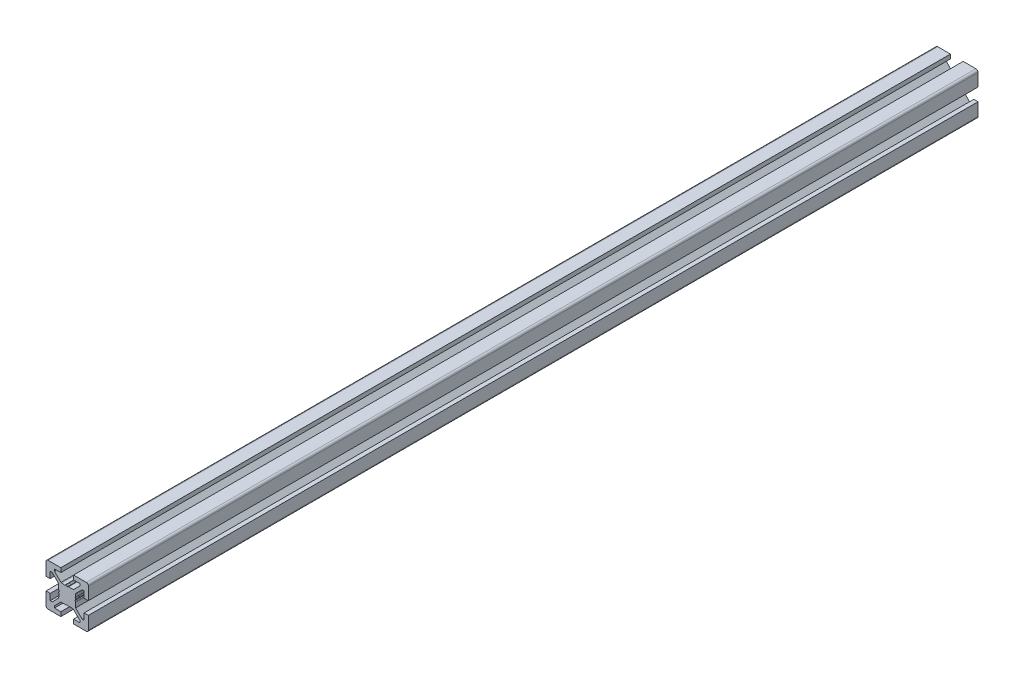
SolidWorks part; units mm, degrees
ref_plane "Front Plane" through (0, 0, 0) normal (0, 0, 1) x (1, 0, 0)
ref_plane "Top Plane" through (0, 0, 0) normal (0, 1, 0) x (1, 0, 0)
ref_plane "Right Plane" through (0, 0, 0) normal (1, 0, 0) x (0, 0, -1)
ref_plane "Plane1" through (0, 0, -2000) normal (0, 0, -1) x (-1, 0, 0)
sketch "Sketch1" plane through (0, 0, -2000) normal (0, 0, -1) x (-1, 0, 0)
  line L0 (10, -3) -> (8, -3)
  line L1 (8, -3) -> (8, -6)
  line L2 (8, -6) -> (7.0607, -6)
  line L3 (7.0607, -6) -> (4, -2.9393)
  line L4 (4, -2.9393) -> (4, -2.5)
  line L5 (4, -2.5) -> (3.751, -1.2189)
  line L6 (3.751, -1.2189) -> (3.933, -0.9036)
  line L7 (3.933, -0.4036) -> (3.7, 0)
  line L8 (3.7, 0) -> (3.933, 0.4036)
  line L9 (4, 0.6536) -> (4, 2.9393)
  line L10 (4, 2.9393) -> (7.0607, 6)
  line L11 (7.0607, 6) -> (8, 6)
  line L12 (8, 6) -> (8, 3)
  line L13 (8, 3) -> (10, 3)
  line L14 (10, 3) -> (10, 9)
  line L15 (9, 10) -> (3, 10)
  line L16 (3, 10) -> (3, 8)
  line L17 (3, 8) -> (6, 8)
  line L18 (6, 8) -> (6, 7.0607)
  line L19 (6, 7.0607) -> (2.9393, 4)
  line L20 (2.9393, 4) -> (2.5, 4)
  line L21 (2.5, 4) -> (1.2189, 3.751)
  line L22 (1.2189, 3.751) -> (0.9036, 3.933)
  line L23 (0.4036, 3.933) -> (0, 3.7)
  line L24 (0, 3.7) -> (-0.4036, 3.933)
  line L25 (-0.6536, 4) -> (-2.9393, 4)
  line L26 (-2.9393, 4) -> (-6, 7.0607)
  line L27 (-6, 7.0607) -> (-6, 8)
  line L28 (-6, 8) -> (-3, 8)
  line L29 (-3, 8) -> (-3, 10)
  line L30 (-3, 10) -> (-9, 10)
  line L31 (-10, 9) -> (-10, 3)
  line L32 (-10, 3) -> (-8, 3)
  line L33 (-8, 3) -> (-8, 6)
  line L34 (-8, 6) -> (-7.0607, 6)
  line L35 (-7.0607, 6) -> (-4, 2.9393)
  line L36 (-4, 2.9393) -> (-4, 2.5)
  line L37 (-4, 2.5) -> (-3.751, 1.2189)
  line L38 (-3.751, 1.2189) -> (-3.933, 0.9036)
  line L39 (-3.933, 0.4036) -> (-3.7, 0)
  line L40 (-3.7, 0) -> (-3.933, -0.4036)
  line L41 (-4, -0.6536) -> (-4, -2.9393)
  line L42 (-4, -2.9393) -> (-7.0607, -6)
  line L43 (-7.0607, -6) -> (-8, -6)
  line L44 (-8, -6) -> (-8, -3)
  line L45 (-8, -3) -> (-10, -3)
  line L46 (-10, -3) -> (-10, -9)
  line L47 (-9, -10) -> (-3, -10)
  line L48 (-3, -10) -> (-3, -8)
  line L49 (-3, -8) -> (-6, -8)
  line L50 (-6, -8) -> (-6, -7.0607)
  line L51 (-6, -7.0607) -> (-2.9393, -4)
  line L52 (-2.9393, -4) -> (-2.5, -4)
  line L53 (-2.5, -4) -> (-1.2189, -3.751)
  line L54 (-1.2189, -3.751) -> (-0.9036, -3.933)
  line L55 (-0.4036, -3.933) -> (0, -3.7)
  line L56 (0, -3.7) -> (0.4036, -3.933)
  line L57 (0.6536, -4) -> (2.9393, -4)
  line L58 (2.9393, -4) -> (6, -7.0607)
  line L59 (6, -7.0607) -> (6, -8)
  line L60 (6, -8) -> (3, -8)
  line L61 (3, -8) -> (3, -10)
  line L62 (3, -10) -> (9, -10)
  line L63 (10, -9) -> (10, -3)
  circle A0 centre (0, 0) radius 2.1
  arc A1 (3.933, -0.9036) -> (3.933, -0.4036) centre (3.5, -0.6536) ccw
  arc A2 (3.933, 0.4036) -> (4, 0.6536) centre (3.5, 0.6536) ccw
  arc A3 (10, 9) -> (9, 10) centre (9, 9) ccw
  arc A4 (0.9036, 3.933) -> (0.4036, 3.933) centre (0.6536, 3.5) ccw
  arc A5 (-0.4036, 3.933) -> (-0.6536, 4) centre (-0.6536, 3.5) ccw
  arc A6 (-9, 10) -> (-10, 9) centre (-9, 9) ccw
  arc A7 (-3.933, 0.9036) -> (-3.933, 0.4036) centre (-3.5, 0.6536) ccw
  arc A8 (-3.933, -0.4036) -> (-4, -0.6536) centre (-3.5, -0.6536) ccw
  arc A9 (-10, -9) -> (-9, -10) centre (-9, -9) ccw
  arc A10 (-0.9036, -3.933) -> (-0.4036, -3.933) centre (-0.6536, -3.5) ccw
  arc A11 (0.4036, -3.933) -> (0.6536, -4) centre (0.6536, -3.5) ccw
  arc A12 (9, -10) -> (10, -9) centre (9, -9) ccw
extrude "Boss-Extrude1" add sketch "Sketch1" against normal blind 400
sketch "草图1" plane through (0, 0, -1600) normal (0, 0, 1) x (1, 0, 0)
  line L64 (-10, -3) -> (-10, -9)
  line L65 (-8, -3) -> (-10, -3)
  line L66 (-8, -6) -> (-8, -3)
  line L67 (-7.0607, -6) -> (-8, -6)
  line L68 (-4, -2.9393) -> (-7.0607, -6)
  line L69 (-4, -2.5) -> (-4, -2.9393)
  line L70 (-3.751, -1.2189) -> (-4, -2.5)
  line L71 (-3.933, -0.9036) -> (-3.751, -1.2189)
  line L72 (-3.7, 0) -> (-3.933, -0.4036)
  line L73 (-3.933, 0.4036) -> (-3.7, 0)
  line L74 (-4, 2.9393) -> (-4, 0.6536)
  line L75 (-7.0607, 6) -> (-4, 2.9393)
  line L76 (-8, 6) -> (-7.0607, 6)
  line L77 (-8, 3) -> (-8, 6)
  line L78 (-10, 3) -> (-8, 3)
  line L79 (-10, 9) -> (-10, 3)
  line L80 (-3, 10) -> (-9, 10)
  line L81 (-3, 8) -> (-3, 10)
  line L82 (-6, 8) -> (-3, 8)
  line L83 (-6, 7.0607) -> (-6, 8)
  line L84 (-2.9393, 4) -> (-6, 7.0607)
  line L85 (-2.5, 4) -> (-2.9393, 4)
  line L86 (-1.2189, 3.751) -> (-2.5, 4)
  line L87 (-0.9036, 3.933) -> (-1.2189, 3.751)
  line L88 (0, 3.7) -> (-0.4036, 3.933)
  line L89 (0.4036, 3.933) -> (0, 3.7)
  line L90 (2.9393, 4) -> (0.6536, 4)
  line L91 (6, 7.0607) -> (2.9393, 4)
  line L92 (6, 8) -> (6, 7.0607)
  line L93 (3, 8) -> (6, 8)
  line L94 (3, 10) -> (3, 8)
  line L95 (9, 10) -> (3, 10)
  line L96 (10, 3) -> (10, 9)
  line L97 (8, 3) -> (10, 3)
  line L98 (8, 6) -> (8, 3)
  line L99 (7.0607, 6) -> (8, 6)
  line L100 (4, 2.9393) -> (7.0607, 6)
  line L101 (4, 2.5) -> (4, 2.9393)
  line L102 (3.751, 1.2189) -> (4, 2.5)
  line L103 (3.933, 0.9036) -> (3.751, 1.2189)
  line L104 (3.7, 0) -> (3.933, 0.4036)
  line L105 (3.933, -0.4036) -> (3.7, 0)
  line L106 (4, -2.9393) -> (4, -0.6536)
  line L107 (7.0607, -6) -> (4, -2.9393)
  line L108 (8, -6) -> (7.0607, -6)
  line L109 (8, -3) -> (8, -6)
  line L110 (10, -3) -> (8, -3)
  line L111 (10, -9) -> (10, -3)
  line L112 (3, -10) -> (9, -10)
  line L113 (3, -8) -> (3, -10)
  line L114 (6, -8) -> (3, -8)
  line L115 (6, -7.0607) -> (6, -8)
  line L116 (2.9393, -4) -> (6, -7.0607)
  line L117 (2.5, -4) -> (2.9393, -4)
  line L118 (1.2189, -3.751) -> (2.5, -4)
  line L119 (0.9036, -3.933) -> (1.2189, -3.751)
  line L120 (0, -3.7) -> (0.4036, -3.933)
  line L121 (-0.4036, -3.933) -> (0, -3.7)
  line L122 (-2.9393, -4) -> (-0.6536, -4)
  line L123 (-6, -7.0607) -> (-2.9393, -4)
  line L124 (-6, -8) -> (-6, -7.0607)
  line L125 (-3, -8) -> (-6, -8)
  line L126 (-3, -10) -> (-3, -8)
  line L127 (-9, -10) -> (-3, -10)
  line L128 (-10, -3) -> (-10, -9)
  line L129 (-8, -3) -> (-10, -3)
  line L130 (-8, -6) -> (-8, -3)
  line L131 (-7.0607, -6) -> (-8, -6)
  line L132 (-4, -2.9393) -> (-7.0607, -6)
  line L133 (-4, -2.5) -> (-4, -2.9393)
  line L134 (-3.751, -1.2189) -> (-4, -2.5)
  line L135 (-3.933, -0.9036) -> (-3.751, -1.2189)
  line L136 (-3.7, 0) -> (-3.933, -0.4036)
  line L137 (-3.933, 0.4036) -> (-3.7, 0)
  line L138 (-4, 2.9393) -> (-4, 0.6536)
  line L139 (-7.0607, 6) -> (-4, 2.9393)
  line L140 (-8, 6) -> (-7.0607, 6)
  line L141 (-8, 3) -> (-8, 6)
  line L142 (-10, 3) -> (-8, 3)
  line L143 (-10, 9) -> (-10, 3)
  line L144 (-3, 10) -> (-9, 10)
  line L145 (-3, 8) -> (-3, 10)
  line L146 (-6, 8) -> (-3, 8)
  line L147 (-6, 7.0607) -> (-6, 8)
  line L148 (-2.9393, 4) -> (-6, 7.0607)
  line L149 (-2.5, 4) -> (-2.9393, 4)
  line L150 (-1.2189, 3.751) -> (-2.5, 4)
  line L151 (-0.9036, 3.933) -> (-1.2189, 3.751)
  line L152 (0, 3.7) -> (-0.4036, 3.933)
  line L153 (0.4036, 3.933) -> (0, 3.7)
  line L154 (2.9393, 4) -> (0.6536, 4)
  line L155 (6, 7.0607) -> (2.9393, 4)
  line L156 (6, 8) -> (6, 7.0607)
  line L157 (3, 8) -> (6, 8)
  line L158 (3, 10) -> (3, 8)
  line L159 (9, 10) -> (3, 10)
  line L160 (10, 3) -> (10, 9)
  line L161 (8, 3) -> (10, 3)
  line L162 (8, 6) -> (8, 3)
  line L163 (7.0607, 6) -> (8, 6)
  line L164 (4, 2.9393) -> (7.0607, 6)
  line L165 (4, 2.5) -> (4, 2.9393)
  line L166 (3.751, 1.2189) -> (4, 2.5)
  line L167 (3.933, 0.9036) -> (3.751, 1.2189)
  line L168 (3.7, 0) -> (3.933, 0.4036)
  line L169 (3.933, -0.4036) -> (3.7, 0)
  line L170 (4, -2.9393) -> (4, -0.6536)
  line L171 (7.0607, -6) -> (4, -2.9393)
  line L172 (8, -6) -> (7.0607, -6)
  line L173 (8, -3) -> (8, -6)
  line L174 (10, -3) -> (8, -3)
  line L175 (10, -9) -> (10, -3)
  line L176 (3, -10) -> (9, -10)
  line L177 (3, -8) -> (3, -10)
  line L178 (6, -8) -> (3, -8)
  line L179 (6, -7.0607) -> (6, -8)
  line L180 (2.9393, -4) -> (6, -7.0607)
  line L181 (2.5, -4) -> (2.9393, -4)
  line L182 (1.2189, -3.751) -> (2.5, -4)
  line L183 (0.9036, -3.933) -> (1.2189, -3.751)
  line L184 (0, -3.7) -> (0.4036, -3.933)
  line L185 (-0.4036, -3.933) -> (0, -3.7)
  line L186 (-2.9393, -4) -> (-0.6536, -4)
  line L187 (-6, -7.0607) -> (-2.9393, -4)
  line L188 (-6, -8) -> (-6, -7.0607)
  line L189 (-3, -8) -> (-6, -8)
  line L190 (-3, -10) -> (-3, -8)
  line L191 (-9, -10) -> (-3, -10)
  arc A12 (-3.933, -0.4036) -> (-3.933, -0.9036) centre (-3.5, -0.6536) ccw
  arc A13 (-4, 0.6536) -> (-3.933, 0.4036) centre (-3.5, 0.6536) ccw
  arc A14 (-9, 10) -> (-10, 9) centre (-9, 9) ccw
  arc A15 (-0.4036, 3.933) -> (-0.9036, 3.933) centre (-0.6536, 3.5) ccw
  arc A16 (0.6536, 4) -> (0.4036, 3.933) centre (0.6536, 3.5) ccw
  arc A17 (10, 9) -> (9, 10) centre (9, 9) ccw
  arc A18 (3.933, 0.4036) -> (3.933, 0.9036) centre (3.5, 0.6536) ccw
  arc A19 (4, -0.6536) -> (3.933, -0.4036) centre (3.5, -0.6536) ccw
  arc A20 (9, -10) -> (10, -9) centre (9, -9) ccw
  arc A21 (0.4036, -3.933) -> (0.9036, -3.933) centre (0.6536, -3.5) ccw
  arc A22 (-0.6536, -4) -> (-0.4036, -3.933) centre (-0.6536, -3.5) ccw
  arc A23 (-10, -9) -> (-9, -10) centre (-9, -9) ccw
  arc A24 (-3.933, -0.4036) -> (-3.933, -0.9036) centre (-3.5, -0.6536) ccw
  arc A25 (-4, 0.6536) -> (-3.933, 0.4036) centre (-3.5, 0.6536) ccw
  arc A26 (-9, 10) -> (-10, 9) centre (-9, 9) ccw
  arc A27 (-0.4036, 3.933) -> (-0.9036, 3.933) centre (-0.6536, 3.5) ccw
  arc A28 (0.6536, 4) -> (0.4036, 3.933) centre (0.6536, 3.5) ccw
  arc A29 (10, 9) -> (9, 10) centre (9, 9) ccw
  arc A30 (3.933, 0.4036) -> (3.933, 0.9036) centre (3.5, 0.6536) ccw
  arc A31 (4, -0.6536) -> (3.933, -0.4036) centre (3.5, -0.6536) ccw
  arc A32 (9, -10) -> (10, -9) centre (9, -9) ccw
  arc A33 (0.4036, -3.933) -> (0.9036, -3.933) centre (0.6536, -3.5) ccw
  arc A34 (-0.6536, -4) -> (-0.4036, -3.933) centre (-0.6536, -3.5) ccw
  arc A35 (-10, -9) -> (-9, -10) centre (-9, -9) ccw
  dimension "D1" = 0
extrude "凸台-拉伸1" add sketch "草图1" along normal blind 20
